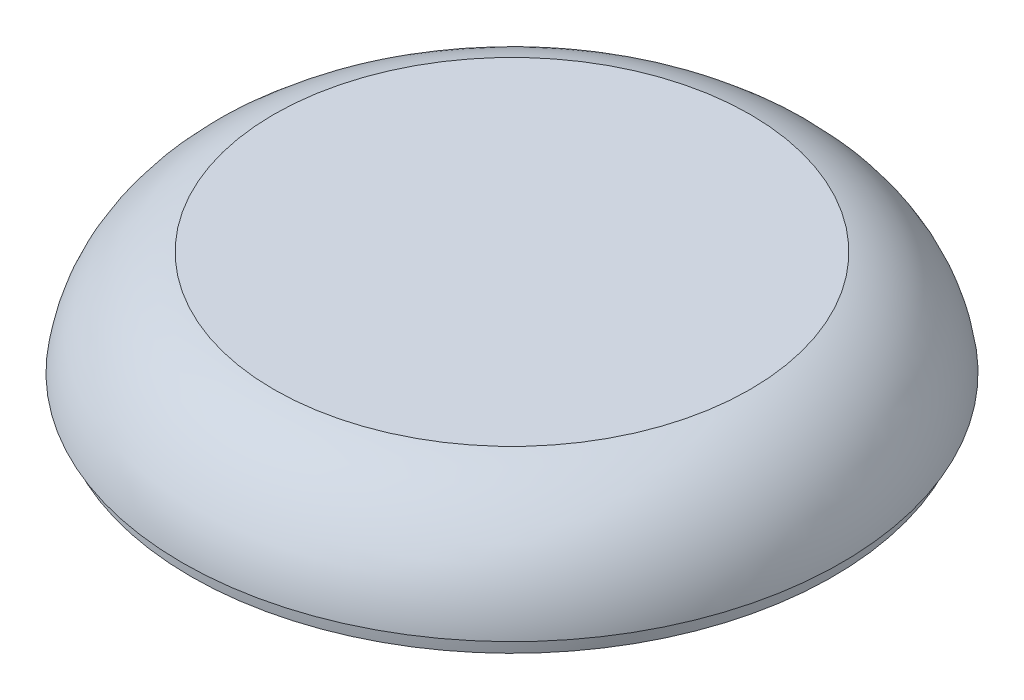
SolidWorks part; units mm, degrees
material "PE Low/Medium Density"
ref_plane "Front Plane" through (0, 0, 0) normal (0, 0, 1) x (1, 0, 0)
ref_plane "Top Plane" through (0, 0, 0) normal (0, 1, 0) x (1, 0, 0)
ref_plane "Right Plane" through (0, 0, 0) normal (1, 0, 0) x (0, 0, -1)
sketch "Sketch1" plane through (0, 0, 0) normal (0, 0, 1) x (1, 0, 0)
  line L13 (0, 0) -> (1, 0)
  line L15 (2.0513, -2) -> (1.05, -2)
  line L17 (11.3645, 13) -> (41, 13)
  line L18 (41, 13) -> (41, 11)
  line L20 (41, 11) -> (11.5705, 11)
  arc A7 (11.3645, 13) -> (0, 0) centre (15.4055, -2) ccw
  arc A8 (1, 0) -> (1.05, -2) centre (41, 0) ccw
  arc A9 (2, 0) -> (2.0513, -2) centre (41, 0) ccw
  arc A10 (11.5705, 11) -> (2, 0) centre (15.4055, -2) ccw
revolve "Revolve3" add sketch "Sketch1" angle 360 about L18
